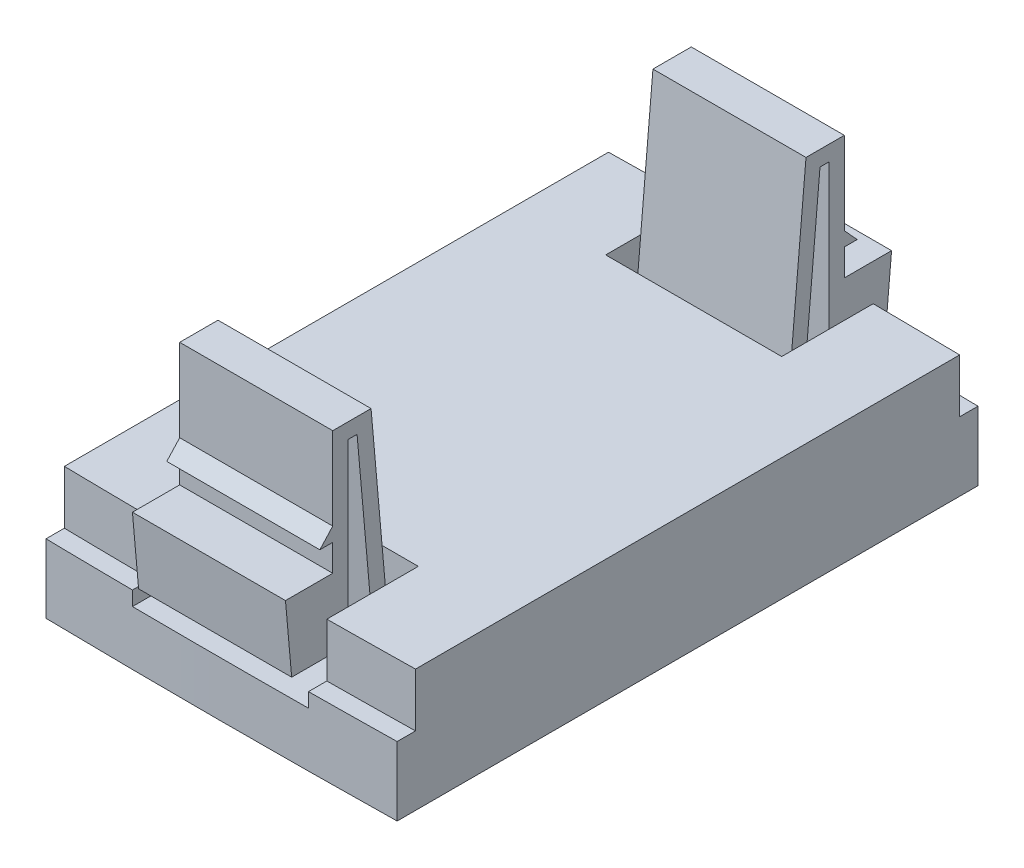
SolidWorks part; units mm, degrees
ref_plane "Front Plane" through (0, 0, 0) normal (0, 0, 1) x (1, 0, 0)
ref_plane "Top Plane" through (0, 0, 0) normal (0, 1, 0) x (1, 0, 0)
ref_plane "Right Plane" through (0, 0, 0) normal (1, 0, 0) x (0, 0, -1)
sketch "Sketch1" plane through (0, 0, 0) normal (0, 1, 0) x (1, 0, 0)
  line L1 (-80, -40) -> (80, -40)
  line L2 (-80, -40) -> (-80, 40)
  line L3 (-80, 40) -> (80, 40)
  line L4 (80, -40) -> (80, 40)
  line L5 (-80, -40) -> (80, 40) construction
  line L6 (-80, 40) -> (80, -40) construction
  point P0 (0, 0)
  dimension "D1" = 80
  dimension "D2" = 160
extrude "Boss-Extrude1" add sketch "Sketch1" along normal blind 8
sketch "Sketch2" plane through (0, 8, 0) normal (0, 1, 0) x (1, 0, 0)
  line L4 (80, -40) -> (80, 40)
  line L5 (80, 40) -> (-80, 40)
  line L6 (-80, 40) -> (-80, -40)
  line L7 (-80, -40) -> (80, -40)
  line L8 (80, -40) -> (80, 40)
  line L9 (80, 40) -> (-80, 40)
  line L10 (-80, 40) -> (-80, -40)
  line L11 (-80, -40) -> (80, -40)
  arc A0 (-73.067, -31.0669) -> (-67.4721, -36.1183) centre (-66.8444, -29.7989) ccw construction
  arc A2 (67.4721, -36.1183) -> (73.067, -31.0669) centre (66.8444, -29.7989) ccw construction
  arc A3 (73.067, -31.0669) -> (73.067, 31.0669) centre (-79.3941, 0) ccw construction
  arc A4 (73.067, 31.0669) -> (67.4721, 36.1183) centre (66.8444, 29.7989) ccw construction
  arc A6 (-67.4721, 36.1183) -> (-73.067, 31.0669) centre (-66.8444, 29.7989) ccw construction
  arc A7 (-73.067, 31.0669) -> (-73.067, -31.0669) centre (79.3941, 0) ccw construction
  arc A8 (-73.067, -31.0669) -> (-67.4721, -36.1183) centre (-66.8444, -29.7989) ccw
  arc A9 (-67.4721, -36.1183) -> (67.4721, -36.1183) centre (0, 643.1485) ccw
  arc A10 (67.4721, -36.1183) -> (73.067, -31.0669) centre (66.8444, -29.7989) ccw
  arc A11 (73.067, -31.0669) -> (73.067, 31.0669) centre (-79.3941, 0) ccw
  arc A12 (73.067, 31.0669) -> (67.4721, 36.1183) centre (66.8444, 29.7989) ccw
  arc A13 (67.4721, 36.1183) -> (-67.4721, 36.1183) centre (0, -643.1485) ccw
  arc A14 (-67.4721, 36.1183) -> (-73.067, 31.0669) centre (-66.8444, 29.7989) ccw
  arc A15 (-73.067, 31.0669) -> (-73.067, -31.0669) centre (79.3941, 0) ccw
  dimension "D1" = 0
extrude "Cut-Extrude1" cut sketch "Sketch2" against normal through all
sketch "Sketch3" plane through (0, 8, 0) normal (0, 1, 0) x (1, 0, 0)
  arc A8 (-71.8911, -30.8273) -> (-67.3535, -34.9241) centre (-66.8444, -29.7989) ccw
  arc A9 (-67.3535, -34.9241) -> (67.3535, -34.9241) centre (0, 643.1485) ccw
  arc A10 (67.3535, -34.9241) -> (71.8911, -30.8273) centre (66.8444, -29.7989) ccw
  arc A11 (71.8911, -30.8273) -> (71.8911, 30.8273) centre (-79.3941, 0) ccw
  arc A12 (71.8911, 30.8273) -> (67.3535, 34.9241) centre (66.8444, 29.7989) ccw
  arc A13 (67.3535, 34.9241) -> (-67.3535, 34.9241) centre (0, -643.1485) ccw
  arc A14 (-67.3535, 34.9241) -> (-71.8911, 30.8273) centre (-66.8444, 29.7989) ccw
  arc A15 (-71.8911, 30.8273) -> (-71.8911, -30.8273) centre (79.3941, 0) ccw
  arc A17 (67.4721, -36.1183) -> (73.067, -31.0669) centre (66.8444, -29.7989) ccw construction
  arc A18 (73.067, -31.0669) -> (73.067, 31.0669) centre (-79.3941, 0) ccw construction
  arc A19 (73.067, 31.0669) -> (67.4721, 36.1183) centre (66.8444, 29.7989) ccw construction
  arc A21 (-67.4721, 36.1183) -> (-73.067, 31.0669) centre (-66.8444, 29.7989) ccw construction
  arc A22 (-73.067, 31.0669) -> (-73.067, -31.0669) centre (79.3941, 0) ccw construction
  arc A23 (-73.067, -31.0669) -> (-67.4721, -36.1183) centre (-66.8444, -29.7989) ccw construction
  arc A24 (-67.4721, -36.1183) -> (67.4721, -36.1183) centre (0, 643.1485) ccw
  arc A25 (67.4721, -36.1183) -> (73.067, -31.0669) centre (66.8444, -29.7989) ccw
  arc A26 (73.067, -31.0669) -> (73.067, 31.0669) centre (-79.3941, 0) ccw
  arc A27 (73.067, 31.0669) -> (67.4721, 36.1183) centre (66.8444, 29.7989) ccw
  arc A28 (67.4721, 36.1183) -> (-67.4721, 36.1183) centre (0, -643.1485) ccw
  arc A29 (-67.4721, 36.1183) -> (-73.067, 31.0669) centre (-66.8444, 29.7989) ccw
  arc A30 (-73.067, 31.0669) -> (-73.067, -31.0669) centre (79.3941, 0) ccw
  arc A31 (-73.067, -31.0669) -> (-67.4721, -36.1183) centre (-66.8444, -29.7989) ccw
sketch "Sketch4" plane through (0, 8, 0) normal (0, 1, 0) x (1, 0, 0)
  line L0 (0, 0) -> (0, -39.4611) construction
sketch "Sketch5" plane through (0, 0, 0) normal (1, 0, 0) x (0, 0, -1)
  line L0 (-42.8898, 4.5) -> (0, 4.5) construction
  line L3 (0, 4.5) -> (0, 0) construction
  line L4 (-33.4233, 4.5) -> (-34.5978, 17.7222)
  line L5 (-34.5978, 17.7222) -> (-37.1018, 17.7222)
  line L6 (-37.1018, 17.7222) -> (-37.1018, 12.3231)
  line L7 (-37.1018, 9.6536) -> (-40.1888, 9.6536)
  line L8 (-34.4272, 4.5) -> (-35.5129, 16.7222)
  line L9 (-35.5129, 16.7222) -> (-36.1018, 16.7222)
  line L10 (-36.1018, 16.7222) -> (-36.1018, 8.6536)
  line L11 (-40.1888, 9.6536) -> (-39.7857, 5.1153)
  line L12 (-34.4194, 4.4115) -> (-35.5129, 16.7222) construction
  line L13 (-34.4272, 4.5) -> (-33.4233, 4.5)
  line L14 (-39.7857, 5.1153) -> (-36.1018, 5.1153)
  line L15 (-36.1018, 8.6536) -> (-40.1888, 8.6536) construction
  line L16 (-36.1018, 5.1153) -> (-36.1018, 8.6536)
  line L17 (-37.1018, 12.3231) -> (-37.9441, 11.4042)
  line L18 (-37.9441, 11.4042) -> (-37.1018, 11.4042)
  line L20 (-37.1018, 11.4042) -> (-37.1018, 9.6536)
  line L21 (-37.1018, 17.7222) -> (-37.1018, 9.6536) construction
  ellipse E0 centre (139.8884, 24.75) end of major axis (139.8884, -153.25) minor radius 177.1283 (-36.1183, 44.75) -> (-36.1183, 4.75) ccw construction
  dimension "D1" = 1
sketch "Sketch6" plane through (0, 8, 0) normal (0, 1, 0) x (1, 0, 0)
  line L1 (-5.25, -43.7611) -> (5.25, -43.7611)
  line L2 (-5.25, -43.7611) -> (-5.25, -32.7611)
  line L3 (-5.25, -32.7611) -> (5.25, -32.7611)
  line L4 (5.25, -43.7611) -> (5.25, -32.7611)
  line L5 (-5.25, -43.7611) -> (5.25, -32.7611) construction
  line L6 (-5.25, -32.7611) -> (5.25, -43.7611) construction
  point P0 (0, -38.2611)
  dimension "D1" = 11
  dimension "D2" = 10.5
sketch "Sketch12" plane through (0, 4.75, 0) normal (0, -1, 0) x (1, 0, 0)
  arc A0 (73.067, -31.0669) -> (73.067, 31.0669) centre (-79.3941, 0) ccw construction
  arc A1 (67.4721, -36.1183) -> (73.067, -31.0669) centre (66.8444, -29.7989) ccw construction
  arc A3 (-73.067, -31.0669) -> (-67.4721, -36.1183) centre (-66.8444, -29.7989) ccw construction
  arc A4 (73.067, -31.0669) -> (73.067, 31.0669) centre (-79.3941, 0) ccw construction
  arc A5 (67.4721, -36.1183) -> (73.067, -31.0669) centre (66.8444, -29.7989) ccw construction
  arc A6 (-67.4721, -36.1183) -> (67.4721, -36.1183) centre (0, 643.1485) ccw construction
  arc A7 (-73.067, -31.0669) -> (-67.4721, -36.1183) centre (-66.8444, -29.7989) ccw construction
  arc A8 (-73.5569, -31.1667) -> (-67.5215, -36.6158) centre (-66.8444, -29.7989) ccw
  arc A9 (-67.5215, -36.6158) -> (67.5215, -36.6158) centre (0, 643.1485) ccw
  arc A10 (67.5215, -36.6158) -> (73.5569, -31.1667) centre (66.8444, -29.7989) ccw
  arc A11 (73.5569, -31.1667) -> (73.5569, 31.1667) centre (-79.3941, 0) ccw
  dimension "D1" = 0.5
extrude "Cut-Extrude5" cut sketch "Sketch3" against normal blind 3.5
extrude "Cut-Extrude6" cut sketch "Sketch6" against normal up to surface (3.5 mm away) up to face at (0, 4.5, 0)
extrude "Boss-Extrude2" add sketch "Sketch5" along normal mid plane 10
sketch "Sketch13" plane through (0, 0, 0) normal (0, 1, 0) x (1, 0, 0)
  line L0 (0, 0) -> (0, -40.1888) construction
  line L1 (5, -40.1888) -> (-5, -40.1888) construction
  line L3 (-11.4707, -59.9878) -> (11.4707, -59.9878)
  line L4 (-11.4707, -59.9878) -> (-11.4707, -20.3899)
  line L5 (-11.4707, -20.3899) -> (11.4707, -20.3899)
  line L6 (11.4707, -59.9878) -> (11.4707, -20.3899)
  line L7 (-11.4707, -59.9878) -> (11.4707, -20.3899) construction
  line L8 (-11.4707, -20.3899) -> (11.4707, -59.9878) construction
  line L9 (-100.2488, -85.9539) -> (102.7083, -85.9539)
  line L10 (-100.2488, -85.9539) -> (-100.2488, 48.8127)
  line L11 (-100.2488, 48.8127) -> (102.7083, 48.8127)
  line L12 (102.7083, -85.9539) -> (102.7083, 48.8127)
extrude "Cut-Extrude7" cut sketch "Sketch13" along normal blind 10
mirror "Mirror2" about plane through (-11.4707, 10, 20.3899) normal (0, 0, 1) of bodies 144
sketch "Sketch14" plane through (0, 8, 0) normal (0, 1, 0) x (1, 0, 0)
  line L0 (-5.75, -38.2408) -> (-5.75, -32.2611)
  line L1 (-5.75, -32.2611) -> (5.75, -32.2611)
  line L2 (5.75, -32.2611) -> (5.75, -38.2408)
  line L3 (-5.75, -38.2408) -> (-5.25, -38.2408)
  line L4 (5.25, -38.2408) -> (5.75, -38.2408)
  line L5 (5.75, -2.539) -> (5.75, -8.5187)
  line L6 (5.75, -8.5187) -> (-5.75, -8.5187)
  line L7 (-5.75, -8.5187) -> (-5.75, -2.539)
  line L8 (11.4707, -38.1645) -> (11.4707, -2.6153)
  line L9 (5.25, -2.539) -> (5.25, -8.0187)
  line L10 (5.25, -8.0187) -> (-5.25, -8.0187)
  line L11 (-5.25, -8.0187) -> (-5.25, -2.539)
  line L12 (-11.4707, -2.6153) -> (-11.4707, -38.1645)
  line L13 (-5.25, -38.2408) -> (-5.25, -32.7611)
  line L14 (-5.25, -32.7611) -> (5.25, -32.7611)
  line L15 (5.25, -32.7611) -> (5.25, -38.2408)
  line L16 (-5.75, -2.539) -> (-5.25, -2.539)
  line L17 (5.25, -2.539) -> (5.25, -8.0187)
  line L18 (5.25, -8.0187) -> (-5.25, -8.0187)
  line L19 (-5.25, -8.0187) -> (-5.25, -2.539)
  line L20 (5.25, -2.539) -> (5.75, -2.539)
  line L21 (-5.25, -38.2408) -> (-5.25, -32.7611)
  line L22 (-5.25, -32.7611) -> (5.25, -32.7611)
  line L23 (5.25, -32.7611) -> (5.25, -38.2408)
  arc A4 (5.25, -38.2408) -> (11.4707, -38.1645) centre (0, 643.1485) ccw
  arc A5 (11.4707, -2.6153) -> (5.25, -2.539) centre (0, -683.9283) ccw
  arc A6 (-5.25, -2.539) -> (-11.4707, -2.6153) centre (0, -683.9283) ccw
  arc A7 (-11.4707, -38.1645) -> (-5.25, -38.2408) centre (0, 643.1485) ccw
  dimension "D1" = 0
  dimension "D2" = 0.5
  dimension "D3" = 0.5
extrude "Cut-Extrude8" cut sketch "Sketch14" along direction (0, 1, 0) on the side against the normal up to surface (3.5 mm away) contours L0 L1 L2 L4 L23 L22 L21 L3 | L7 L16 L19 L18 L17 L20 L5 L6
sketch "Sketch16" plane through (0, 0, 37.1018) normal (0, 0, 1) x (1, 0, 0)
  line L0 (-5.75, 4.5) -> (-5.75, 3.5636)
  line L1 (-5.75, 3.5636) -> (5.75, 3.5636)
  line L2 (5.75, 3.5636) -> (5.75, 4.5)
  line L3 (5.75, 4.5) -> (-5.75, 4.5)
extrude "Cut-Extrude9" cut sketch "Sketch16" against normal blind 2 and the other way blind 10
ref_plane "Plane1" through (0, 0, 20.3899) normal (0, 0, 1) x (1, 0, 0)
mirror "Mirror3" about plane through (0, 0, 20.3899) normal (0, 0, 1) of "Cut-Extrude9"
